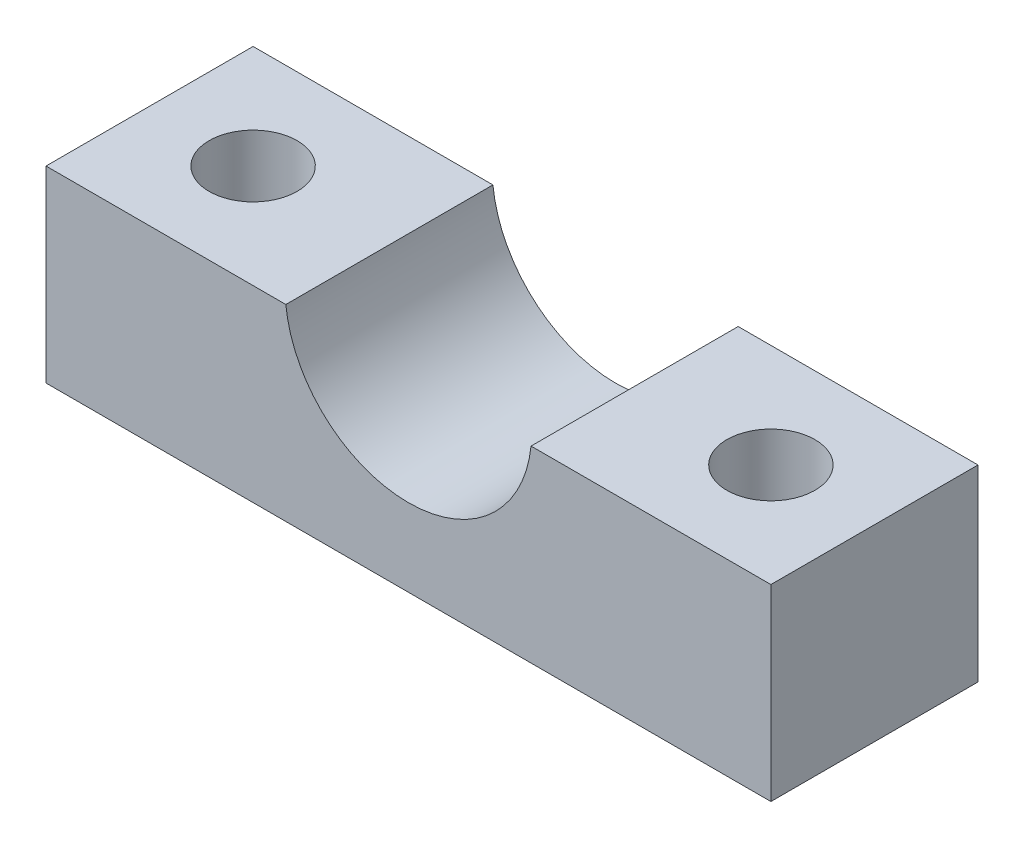
SolidWorks part; units mm, degrees
ref_plane "Front Plane" through (0, 0, 0) normal (0, 0, 1) x (1, 0, 0)
ref_plane "Top Plane" through (0, 0, 0) normal (0, 1, 0) x (1, 0, 0)
ref_plane "Right Plane" through (0, 0, 0) normal (1, 0, 0) x (0, 0, -1)
sketch "Sketch1" plane through (0, 0, 0) normal (0, 0, 1) x (1, 0, 0)
  line L0 (0, 0) -> (0, -0.5) construction
  line L1 (14, -0.5) -> (4.7362, -0.5)
  line L2 (14, -0.5) -> (14, -7.76)
  line L3 (14, -7.76) -> (-14, -7.76)
  line L4 (-14, -0.5) -> (-14, -7.76)
  line L5 (-4.7362, -0.5) -> (-14, -0.5)
  arc A0 (-4.7362, -0.5) -> (4.7362, -0.5) centre (0, 0) ccw
  dimension "D2" = 9.525
  dimension "D1" = 0.5
  dimension "D3" = 7.76
  dimension "D4" = 28
extrude "Boss-Extrude1" add sketch "Sketch1" along normal mid plane 8
sketch "Sketch2" plane through (0, -7.76, 0) normal (0, -1, 0) x (1, 0, 0)
  line L0 (-10, 0) -> (10, 0) construction
  dimension "D1" = 20
hole_wizard "M3 Clearance Hole1" positions "Sketch4" profile "Sketch3" hole size "M3" standard "Ansi Metric" end condition through all
sketch "Sketch4" plane through (0, -7.76, 0) normal (0, -1, 0) x (1, 0, 0)
  point P0 (-10, 0)
  point P1 (10, 0)
sketch "Sketch3" plane through (-10, -7.76, 0) normal (1, 0, 0) x (0, 0, -1)
  line L0 (0, 0) -> (0, 7.26)
  line L1 (0, 7.26) -> (1.7, 7.26)
  line L2 (1.7, 7.26) -> (1.7, 0)
  line L5 (1.7, 0) -> (0, 0)
  line L11 (0, -6.35) -> (0, 107.95) construction
  dimension "Thru Hole Dia." = 3.4
  dimension "Thru Hole Depth" = 7.26
sketch "Sketch5" plane through (0, -7.76, 0) normal (0, -1, 0) x (1, 0, 0)
  line L1 (-7.25, -1.5877) -> (-7.25, 1.5877)
  line L2 (-7.25, 1.5877) -> (-10, 3.1754)
  line L3 (-10, 3.1754) -> (-12.75, 1.5877)
  line L4 (-12.75, 1.5877) -> (-12.75, -1.5877)
  line L5 (-12.75, -1.5877) -> (-10, -3.1754)
  line L6 (-10, -3.1754) -> (-7.25, -1.5877)
  line L7 (7.25, -1.5877) -> (10, -3.1754)
  line L8 (10, -3.1754) -> (12.75, -1.5877)
  line L9 (12.75, -1.5877) -> (12.75, 1.5877)
  line L10 (12.75, 1.5877) -> (10, 3.1754)
  line L11 (10, 3.1754) -> (7.25, 1.5877)
  line L12 (7.25, 1.5877) -> (7.25, -1.5877)
  circle A0 centre (-10, 0) radius 2.75 construction
  circle A1 centre (10, 0) radius 2.75 construction
  dimension "D1" = 5.5
extrude "Cut-Extrude1" cut sketch "Sketch5" against normal blind 3
